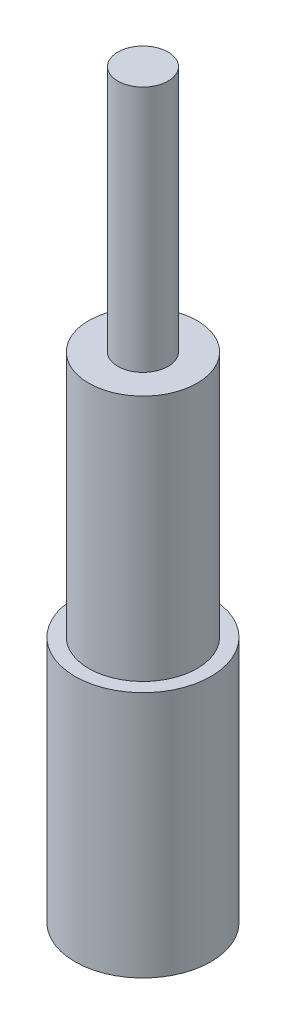
SolidWorks part; units mm, degrees
ref_plane "Front Plane" through (0, 0, 0) normal (0, 0, 1) x (1, 0, 0)
ref_plane "Top Plane" through (0, 0, 0) normal (0, 1, 0) x (1, 0, 0)
ref_plane "Right Plane" through (0, 0, 0) normal (1, 0, 0) x (0, 0, -1)
sketch "Sketch1" plane through (0, 0, 0) normal (0, 1, 0) x (1, 0, 0)
  circle A0 centre (0, 0) radius 5.5
  dimension "D1" = 11
extrude "Boss-Extrude1" add sketch "Sketch1" along normal blind 20
sketch "Sketch2" plane through (0, 20, 0) normal (0, 1, 0) x (1, 0, 0)
  circle A0 centre (0, 0) radius 4.388
extrude "Boss-Extrude2" add sketch "Sketch2" along normal blind 20
sketch "Sketch3" plane through (0, 40, 0) normal (0, 1, 0) x (1, 0, 0)
  circle A0 centre (0, 0) radius 2.0358
extrude "Boss-Extrude3" add sketch "Sketch3" along normal blind 20
